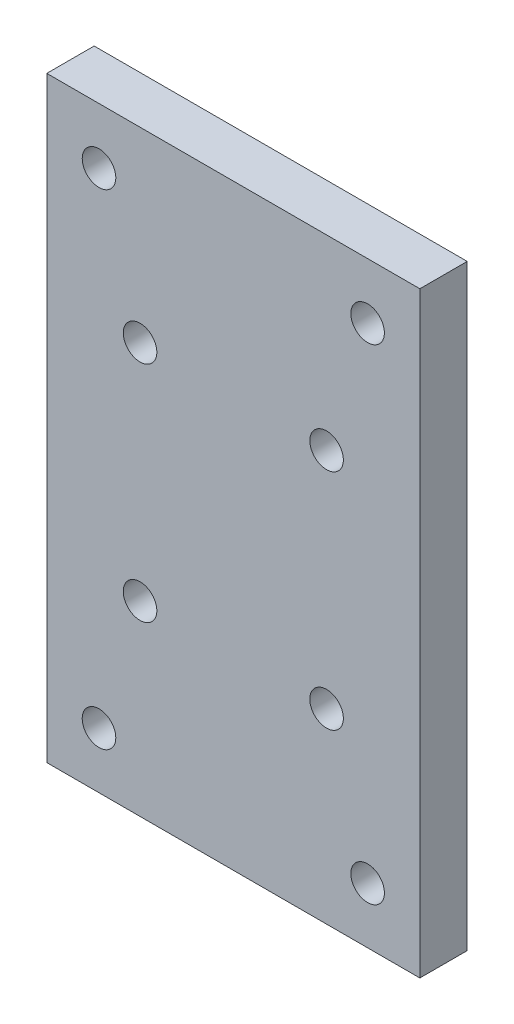
SolidWorks part; units mm, degrees
ref_plane "Alzado" through (0, 0, 0) normal (0, 0, 1) x (1, 0, 0)
ref_plane "Planta" through (0, 0, 0) normal (0, 1, 0) x (1, 0, 0)
ref_plane "Vista lateral" through (0, 0, 0) normal (1, 0, 0) x (0, 0, -1)
sketch "Sketch1" plane through (0, 0, 0) normal (0, 0, 1) x (1, 0, 0)
  line L1 (0, 0) -> (100, 0)
  line L2 (0, 0) -> (0, 160)
  line L3 (0, 160) -> (100, 160)
  line L4 (100, 0) -> (100, 160)
  dimension "D1" = 160
  dimension "D2" = 100
extrude "Boss-Extrude1" add sketch "Sketch1" along normal blind 12.7
sketch "Sketch2" plane through (0, 0, 12.7) normal (0, 0, 1) x (-1, 0, 0)
  line L0 (-100, 0) -> (-100, -160) construction
  line L1 (-100, 0) -> (-100, -160) construction
  line L2 (-100, -80) -> (0, -80) construction
  line L3 (-50, -20) -> (-50, -100) construction
  line L4 (0, -160) -> (0, 0) construction
  line L5 (0, -30) -> (-100, -30) construction
  line L6 (-50, 0) -> (-50, -160) construction
  line L7 (-100, -160) -> (0, -160) construction
  line L12 (0, -130) -> (-100, -130) construction
  circle A6 centre (-75, -110) radius 4.5
  circle A7 centre (-25, -110) radius 4.5
  circle A8 centre (-25, -50) radius 4.5
  circle A9 centre (-75, -50) radius 4.5
  dimension "D7" = 9
  dimension "D8" = 9
  dimension "D2" = 25
  dimension "D3" = 25
  dimension "D4" = 25
  dimension "D5" = 30
  dimension "D6" = 30
  dimension "D1" = 25
  dimension "D9" = 30
  dimension "D10" = 30
  dimension "D11" = 25
  dimension "D12" = 25
  dimension "D13" = 50
  dimension "D14" = 50
extrude "Cut-Extrude1" cut sketch "Sketch2" against normal up to surface (12.7 mm away) contours A6 | A7 | A8 | A9 up to face at (50, 80, 0)
sketch "Sketch3" plane through (0, 0, 12.7) normal (0, 0, 1) x (1, 0, 0)
  line L0 (100, 0) -> (100, 160) construction
  line L1 (0, 0) -> (100, 0) construction
  line L2 (0, 0) -> (0, 30) construction
  line L3 (0, 30) -> (100, 30) construction
  line L4 (100, 0) -> (100, 30) construction
  line L5 (0, 30) -> (14, 30) construction
  line L6 (14, 30) -> (14, 15) construction
  line L7 (0, 30) -> (14, 30) construction
  line L8 (100, 30) -> (86, 30) construction
  line L9 (86, 30) -> (86, 15) construction
  line L10 (100, 80) -> (0, 80) construction
  line L11 (0, 160) -> (0, 0) construction
  circle A0 centre (14, 15) radius 4.5
  circle A1 centre (86, 15) radius 4.5
  circle A2 centre (14, 145) radius 4.5
  circle A3 centre (86, 145) radius 4.5
  dimension "D6" = 9
  dimension "D7" = 9
  dimension "D1" = 30
  dimension "D2" = 15
  dimension "D3" = 14
  dimension "D4" = 14
  dimension "D5" = 15
extrude "Cut-Extrude2" cut sketch "Sketch3" against normal up to surface (12.7 mm away) contours A1 | A0 | A3 | A2 up to face at (20.5, 50, 0)
